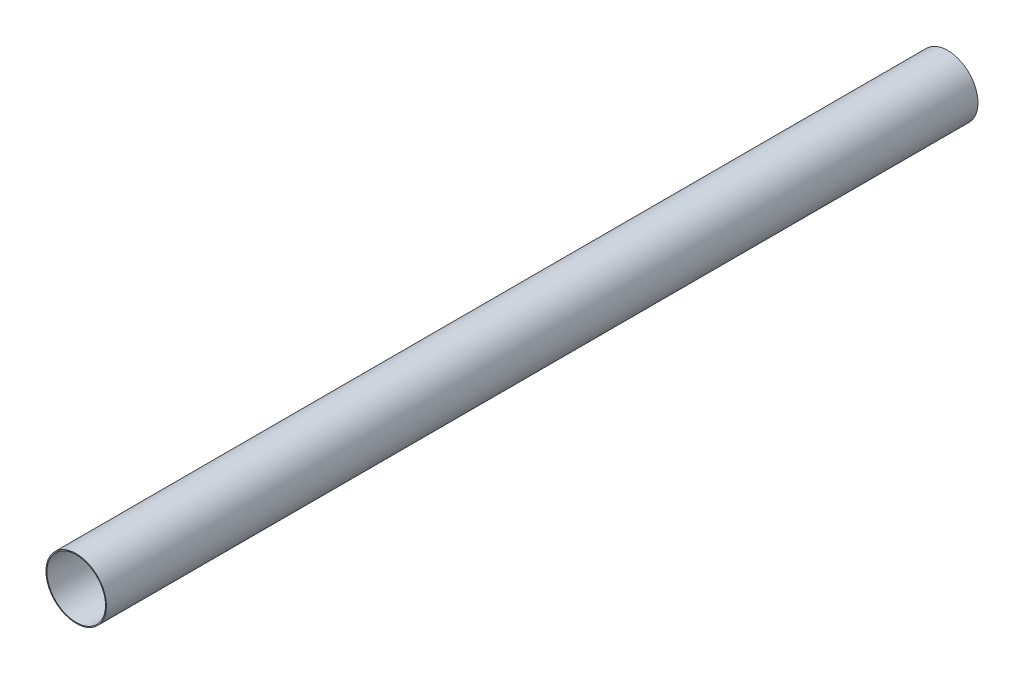
SolidWorks part; units mm, degrees
ref_plane "Front Plane" through (0, 0, 0) normal (0, 0, 1) x (1, 0, 0)
ref_plane "Top Plane" through (0, 0, 0) normal (0, 1, 0) x (1, 0, 0)
ref_plane "Right Plane" through (0, 0, 0) normal (1, 0, 0) x (0, 0, -1)
sketch "Sketch1" plane through (0, 0, 0) normal (0, 0, 1) x (1, 0, 0)
  circle A0 centre (0, 0) radius 51.1175
  circle A1 centre (0, 0) radius 49.53
  dimension "D1" = 102.235
  dimension "D2" = 1.5875
extrude "Boss-Extrude1" add sketch "Sketch1" along normal blind 1473.2
